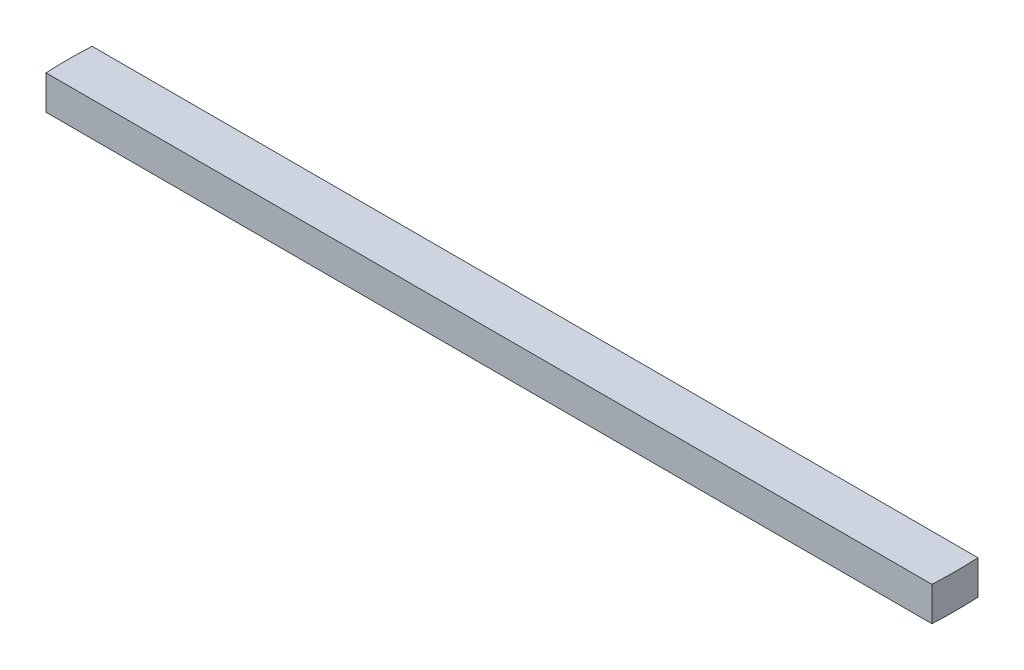
SolidWorks part; units mm, degrees
ref_plane "Front Plane" through (0, 0, 0) normal (0, 0, 1) x (1, 0, 0)
ref_plane "Top Plane" through (0, 0, 0) normal (0, 1, 0) x (1, 0, 0)
ref_plane "Right Plane" through (0, 0, 0) normal (1, 0, 0) x (0, 0, -1)
sketch "Sketch1" plane through (0, 0, 0) normal (0, 1, 0) x (1, 0, 0)
  line L0 (-1978.5268, 102.8834) -> (1978.5268, 102.8834)
  line L1 (-55, 0) -> (55, 0) construction
  line L2 (-1978.5268, -102.8834) -> (1978.5268, -102.8834)
  arc A0 (-1978.5268, 102.8834) -> (-1978.5268, -102.8834) centre (0, 0) ccw
  arc A1 (1978.5268, -102.8834) -> (1978.5268, 102.8834) centre (0, 0) ccw
  dimension "D1" = 3962.4
extrude "Boss-Extrude1" add sketch "Sketch1" along normal blind 152.4
